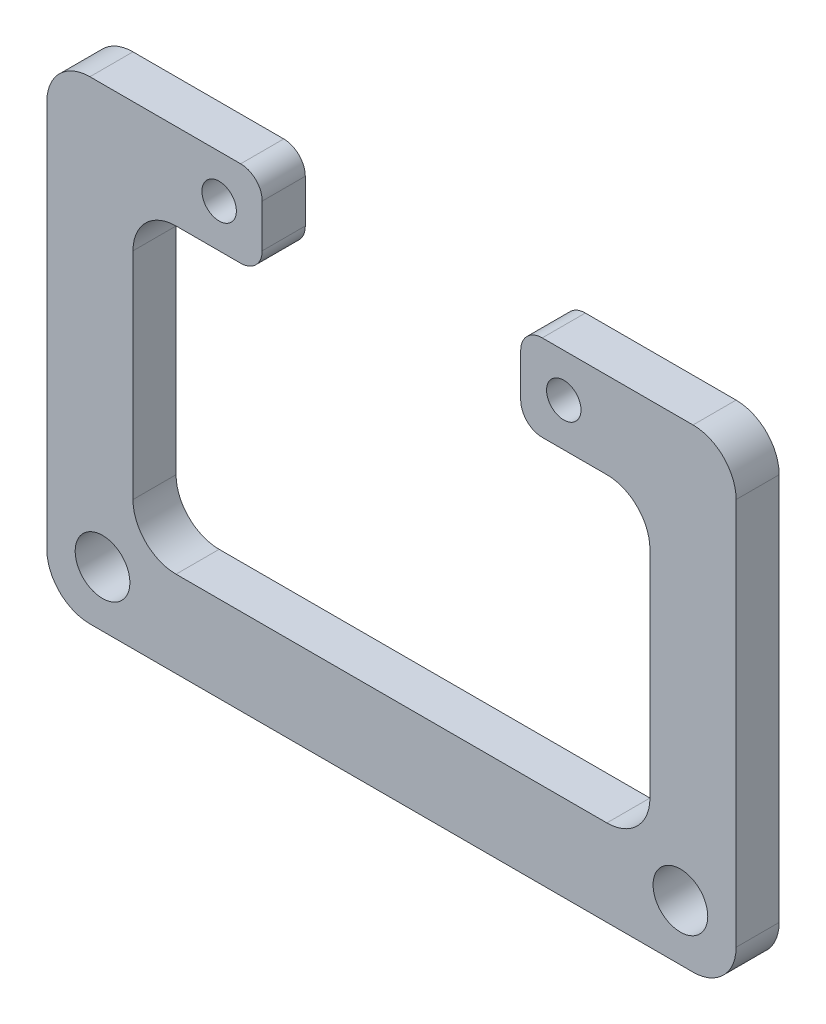
SolidWorks part; units mm, degrees
ref_plane "Front Plane" through (0, 0, 0) normal (0, 0, 1) x (1, 0, 0)
ref_plane "Top Plane" through (0, 0, 0) normal (0, 1, 0) x (1, 0, 0)
ref_plane "Right Plane" through (0, 0, 0) normal (1, 0, 0) x (0, 0, -1)
sketch "Sketch1" plane through (0, 0, 0) normal (0, 0, 1) x (1, 0, 0)
  line L0 (0, 0) -> (80, 0)
  line L1 (80, 0) -> (80, 110)
  line L2 (80, 110) -> (30, 110)
  line L3 (30, 110) -> (30, 90)
  line L4 (30, 90) -> (60, 90)
  line L5 (60, 90) -> (60, 20)
  line L6 (60, 20) -> (0, 20)
  line L7 (0, 20) -> (0, 0)
  line L8 (0, 20) -> (0, 125.8407) construction
  line L9 (67.0711, 12.9289) -> (57.0711, 22.9289) construction
  line L10 (67.0711, 12.9289) -> (77.0711, 2.9289) construction
  circle A0 centre (40, 100) radius 10
  circle A1 centre (40, 100) radius 4
  circle A2 centre (67.0711, 12.9289) radius 6.35
  arc A3 (70, 0) -> (80, 10) centre (70, 10) ccw
  arc A4 (50, 20) -> (60, 30) centre (50, 30) ccw
  dimension "D3" = 20
  dimension "D4" = 8
  dimension "D8" = 12.7
  dimension "D9" = 10
  dimension "D1" = 20
  dimension "D2" = 20
  dimension "D5" = 40
  dimension "D6" = 50
  dimension "D7" = 70
extrude "Boss-Extrude1" add sketch "Sketch1" against normal mid plane 10 contours A0 L4 L5 L6 L7 L0 L1 L2 A2 | A0 L2 L3 | A0 A1 | A0 L3 L4 | A4 L6 L5
mirror "Mirror1" about plane through (0, 0, -5) normal (-1, 0, 0) of "Boss-Extrude1"
fillet "Fillet1" radius 10 4 edges at (80, 110, 0) (60, 90, 0) (-60, 90, 0) (-80, 110, 0)
fillet "Fillet2" radius 5 4 edges at (30, 110, 0) (30, 90, 0) (-30, 110, 0) (-30, 90, 0)
